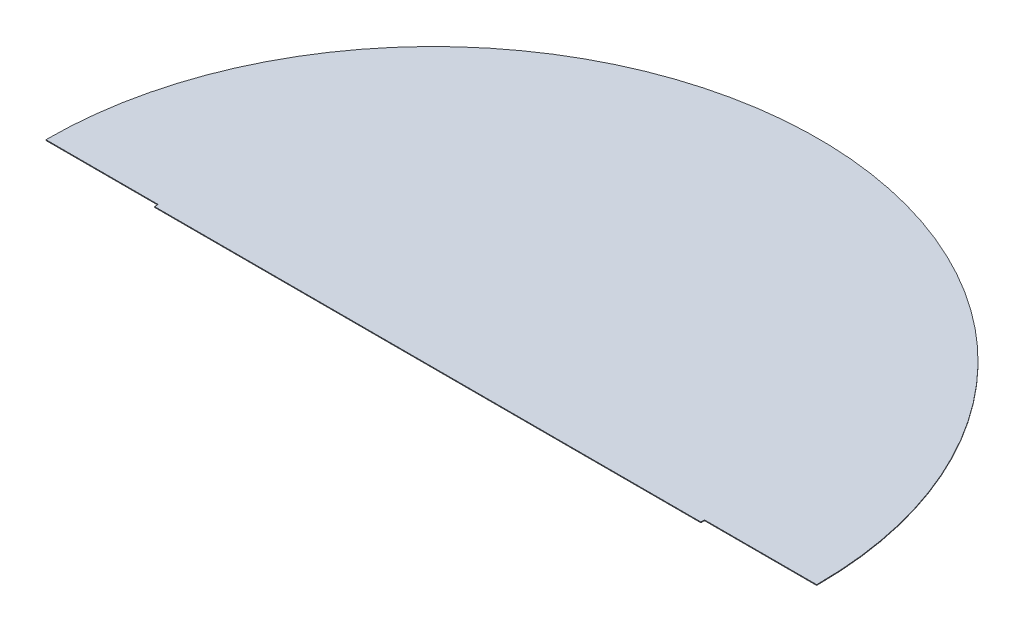
SolidWorks part; units mm, degrees
ref_plane "Front Plane" through (0, 0, 0) normal (0, 0, 1) x (1, 0, 0)
ref_plane "Top Plane" through (0, 0, 0) normal (0, 1, 0) x (1, 0, 0)
ref_plane "Right Plane" through (0, 0, 0) normal (1, 0, 0) x (0, 0, -1)
sketch "Sketch1" plane through (0, 0, 0) normal (0, 1, 0) x (1, 0, 0)
  line L0 (0, 0) -> (0, -5)
  line L1 (310, -15) -> (1820, -15)
  line L2 (2130, -5) -> (2130, 0)
  line L6 (0, -5) -> (310, -5)
  line L7 (310, -15) -> (310, -5)
  line L10 (2130, -5) -> (1820, -5)
  line L11 (1820, -15) -> (1820, -5)
  arc A0 (0, 0) -> (2130, 0) centre (1065, 0) cw
  dimension "D1" = 1065
  dimension "D3" = 5
  dimension "D4" = 310
  dimension "D5" = 5
  dimension "D6" = 310
extrude "Boss-Extrude1" add sketch "Sketch1" along normal blind 2
